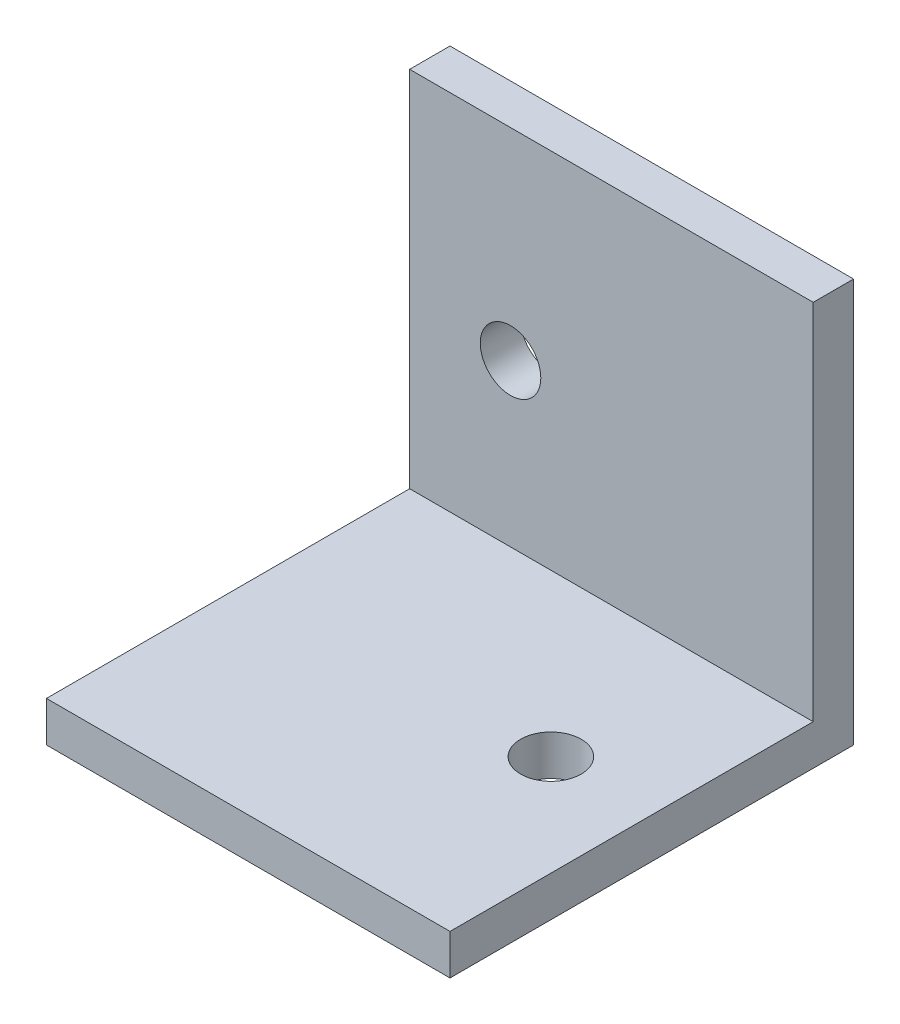
SolidWorks part; units mm, degrees
ref_plane "前视基准面" through (0, 0, 0) normal (0, 0, 1) x (1, 0, 0)
ref_plane "上视基准面" through (0, 0, 0) normal (0, 1, 0) x (1, 0, 0)
ref_plane "右视基准面" through (0, 0, 0) normal (1, 0, 0) x (0, 0, -1)
sketch "草图1" plane through (0, 0, 0) normal (0, 0, 1) x (1, 0, 0)
  line L1 (-10, 10) -> (10, 10)
  line L2 (-10, 10) -> (-10, -10)
  line L3 (-10, -10) -> (10, -10)
  line L4 (10, 10) -> (10, -10)
  line L5 (-10, 10) -> (10, -10) construction
  line L6 (-10, -10) -> (10, 10) construction
  point P0 (0, 0)
  dimension "D1" = 20
  dimension "D2" = 20
extrude "凸台-拉伸1" add sketch "草图1" along normal blind 2
sketch "草图2" plane through (0, 0, 2) normal (0, 0, 1) x (1, 0, 0)
  line L0 (10, -10) -> (10, 10) construction
  line L1 (-10, -10) -> (10, -10)
  line L2 (-10, -10) -> (-10, -8)
  line L3 (-10, -8) -> (10, -8)
  line L4 (10, -10) -> (10, -8)
  dimension "D1" = 2
extrude "凸台-拉伸2" add sketch "草图2" along normal blind 18
sketch "草图3" plane through (0, 0, 2) normal (0, 0, 1) x (1, 0, 0)
  line L3 (-10, 10) -> (-10, -8) construction
  line L4 (10, 10) -> (-10, 10) construction
  circle A0 centre (-5, 0) radius 1.5
  dimension "D1" = 3
  dimension "D2" = 5
  dimension "D3" = 10
extrude "切除-拉伸1" cut sketch "草图3" against normal blind 10
sketch "草图4" plane through (0, -8, 0) normal (0, 1, 0) x (1, 0, 0)
  line L4 (10, -20) -> (-10, -20) construction
  line L5 (10, -20) -> (10, -2) construction
  circle A1 centre (5, -10) radius 1.5
  point P4 (2.8845, -10.6446)
  dimension "D1" = 10
  dimension "D2" = 3
  dimension "D3" = 5
extrude "切除-拉伸2" cut sketch "草图4" against normal blind 10
